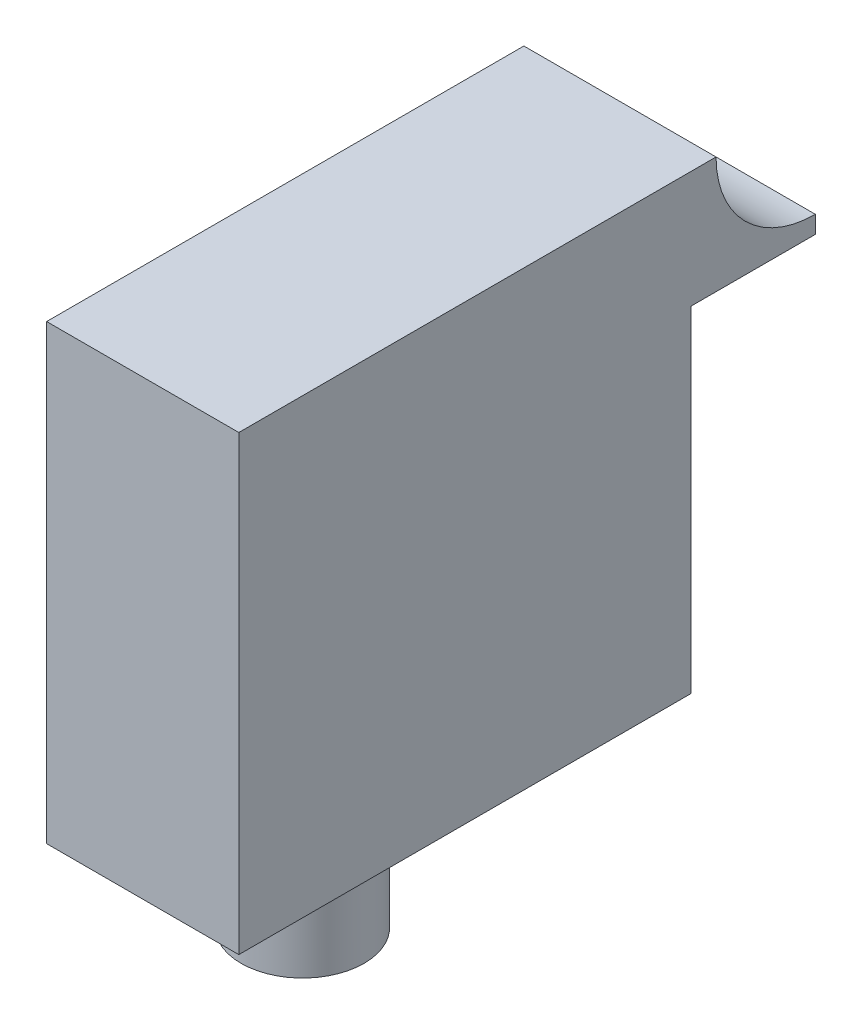
SolidWorks part; units mm, degrees
ref_plane "Спереди" through (0, 0, 0) normal (0, 0, 1) x (1, 0, 0)
ref_plane "Сверху" through (0, 0, 0) normal (0, 1, 0) x (1, 0, 0)
ref_plane "Справа" through (0, 0, 0) normal (1, 0, 0) x (0, 0, -1)
sketch "Эскиз1" plane through (0, 0, 0) normal (1, 0, 0) x (0, 0, -1)
  line L1 (-20, -20) -> (20, -20)
  line L2 (-20, -20) -> (-20, 20)
  line L3 (-20, 20) -> (20, 20)
  line L4 (20, -20) -> (20, 20)
  line L5 (-20, -20) -> (20, 20) construction
  line L6 (-20, 20) -> (20, -20) construction
  point P0 (0, 0)
  dimension "D1" = 40
  dimension "D2" = 40
extrude "Бобышка-Вытянуть1" add sketch "Эскиз1" along normal blind 17
sketch "Эскиз2" plane through (17, 0, 0) normal (1, 0, 0) x (0, 0, -1)
  line L8 (19.5, -19.5) -> (19.5, 19.5)
  line L9 (19.5, 19.5) -> (-19.5, 19.5)
  line L10 (-19.5, 19.5) -> (-19.5, -19.5)
  line L11 (-19.5, -19.5) -> (19.5, -19.5)
  line L12 (19.5, -19.5) -> (19.5, 19.5)
  line L13 (19.5, 19.5) -> (-19.5, 19.5)
  line L14 (-19.5, 19.5) -> (-19.5, -19.5)
  line L15 (-19.5, -19.5) -> (19.5, -19.5)
  dimension "D1" = 0.5
extrude "Бобышка-Вытянуть2" add sketch "Эскиз2" along normal blind 11
sketch "Эскиз3" plane through (28, 0, 0) normal (1, 0, 0) x (0, 0, -1)
  line L0 (19.5, 19.5) -> (-19.5, 19.5) construction
  line L3 (-17, 19.5) -> (-15, 19.5)
  line L4 (-17, 19.5) -> (-17, -19.5)
  line L5 (-17, -19.5) -> (-15, -19.5)
  line L7 (-15, 19.5) -> (-15, -19.5)
  line L8 (-19.5, -19.5) -> (19.5, -19.5) construction
  line L9 (-19.5, 19.5) -> (-19.5, -19.5) construction
  line L10 (-11, 19.5) -> (-11, -19.5)
  line L11 (-13, 19.5) -> (-11, 19.5)
  line L12 (-13, 19.5) -> (-13, -19.5)
  line L13 (-13, -19.5) -> (-11, -19.5)
  line L14 (-7, 19.5) -> (-7, -19.5)
  line L15 (-9, 19.5) -> (-7, 19.5)
  line L16 (-9, 19.5) -> (-9, -19.5)
  line L17 (-9, -19.5) -> (-7, -19.5)
  line L18 (-3, 19.5) -> (-3, -19.5)
  line L19 (-5, 19.5) -> (-3, 19.5)
  line L20 (-5, 19.5) -> (-5, -19.5)
  line L21 (-5, -19.5) -> (-3, -19.5)
  line L22 (1, 19.5) -> (1, -19.5)
  line L23 (-1, 19.5) -> (1, 19.5)
  line L24 (-1, 19.5) -> (-1, -19.5)
  line L25 (-1, -19.5) -> (1, -19.5)
  line L26 (5, 19.5) -> (5, -19.5)
  line L27 (3, 19.5) -> (5, 19.5)
  line L28 (3, 19.5) -> (3, -19.5)
  line L29 (3, -19.5) -> (5, -19.5)
  line L30 (9, 19.5) -> (9, -19.5)
  line L31 (7, 19.5) -> (9, 19.5)
  line L32 (7, 19.5) -> (7, -19.5)
  line L33 (7, -19.5) -> (9, -19.5)
  line L34 (13, 19.5) -> (13, -19.5)
  line L35 (11, 19.5) -> (13, 19.5)
  line L36 (11, 19.5) -> (11, -19.5)
  line L37 (11, -19.5) -> (13, -19.5)
  line L38 (17, 19.5) -> (17, -19.5)
  line L39 (15, 19.5) -> (17, 19.5)
  line L40 (15, 19.5) -> (15, -19.5)
  line L41 (15, -19.5) -> (17, -19.5)
  dimension "D1" = 2.5
  dimension "D2" = 2
  dimension "D3" = 9
extrude "Вырез-Вытянуть1" cut sketch "Эскиз3" against normal blind 9
sketch "Эскиз4" plane through (28, 0, 0) normal (1, 0, 0) x (0, 0, -1)
  line L1 (13.9411, 18.5341) -> (-13.9658, 18.5341)
  line L2 (18.9411, 13.5341) -> (18.9411, -13.7943)
  line L3 (13.9411, -18.7943) -> (-13.9658, -18.7943)
  line L4 (-18.9658, 13.5341) -> (-18.9658, -13.7943)
  arc A0 (-13.9658, -18.7943) -> (-18.9658, -13.7943) centre (-13.9658, -13.7943) cw
  arc A1 (18.9411, -13.7943) -> (13.9411, -18.7943) centre (13.9411, -13.7943) cw
  arc A2 (13.9411, 18.5341) -> (18.9411, 13.5341) centre (13.9411, 13.5341) cw
  arc A3 (-13.9658, 18.5341) -> (-18.9658, 13.5341) centre (-13.9658, 13.5341) ccw
  dimension "D1" = 5
extrude "Бобышка-Вытянуть3" add sketch "Эскиз4" along normal blind 11
sketch "Эскиз5" plane through (0, -20, 0) normal (0, -1, 0) x (1, 0, 0)
  circle A0 centre (7.7671, 5.1283) radius 5.4447
extrude "Бобышка-Вытянуть4" add sketch "Эскиз5" along normal blind 11
sketch "Эскиз6" plane through (0, -31, 0) normal (0, -1, 0) x (1, 0, 0)
  line L1 (-1.8317, 13.8454) -> (23.1683, 13.8454)
  line L2 (-1.8317, 13.8454) -> (-1.8317, -3.5373)
  line L3 (-1.8317, -3.5373) -> (23.1683, -3.5373)
  line L4 (23.1683, 13.8454) -> (23.1683, -3.5373)
  line L5 (-1.8317, 13.8454) -> (23.1683, -3.5373) construction
  line L6 (-1.8317, -3.5373) -> (23.1683, 13.8454) construction
  point P0 (10.6683, 5.1541)
  dimension "D1" = 17.3827
  dimension "D2" = 25
extrude "Бобышка-Вытянуть5" add sketch "Эскиз6" along normal blind 11
sketch "Эскиз7" plane through (0, -42, 0) normal (0, -1, 0) x (1, 0, 0)
  circle A0 centre (7.7101, 5.1075) radius 4.5
extrude "Бобышка-Вытянуть6" add sketch "Эскиз7" along normal blind 11 draft 17
sketch "Эскиз8" plane through (0, 0, -20) normal (0, 0, -1) x (-1, 0, 0)
  line L0 (0, -20) -> (0, 20) construction
  line L1 (-17, 20) -> (0, 20)
  line L2 (-17, 20) -> (-17, 9.6758)
  line L3 (-17, 9.6758) -> (0, 9.6758)
  line L4 (0, 20) -> (0, 9.6758)
extrude "Бобышка-Вытянуть7" add sketch "Эскиз8" along normal blind 11
sketch "Эскиз9" plane through (17, 0, 0) normal (1, 0, 0) x (0, 0, -1)
  circle A0 centre (31, 20) radius 8.7844
extrude "Вырез-Вытянуть2" cut sketch "Эскиз9" against normal blind 27
sketch "Эскиз10" plane through (0, -20, 0) normal (0, -1, 0) x (1, 0, 0)
  line L1 (-24.4627, 31.2371) -> (34.015, 31.2371)
  line L2 (-24.4627, 31.2371) -> (-24.4627, -39.556)
  line L3 (-24.4627, -39.556) -> (34.015, -39.556)
  line L4 (34.015, 31.2371) -> (34.015, -39.556)
extrude "Вырез-Вытянуть3" cut sketch "Эскиз10" along normal blind 47 from offset 10
sketch "Эскиз11" plane through (39, 0, 0) normal (1, 0, 0) x (0, 0, -1)
  line L1 (-25.8065, -33.4423) -> (36.9441, -33.4423)
  line L2 (-25.8065, -33.4423) -> (-25.8065, 46.7761)
  line L3 (-25.8065, 46.7761) -> (36.9441, 46.7761)
  line L4 (36.9441, -33.4423) -> (36.9441, 46.7761)
extrude "Вырез-Вытянуть4" cut sketch "Эскиз11" against normal blind 22
